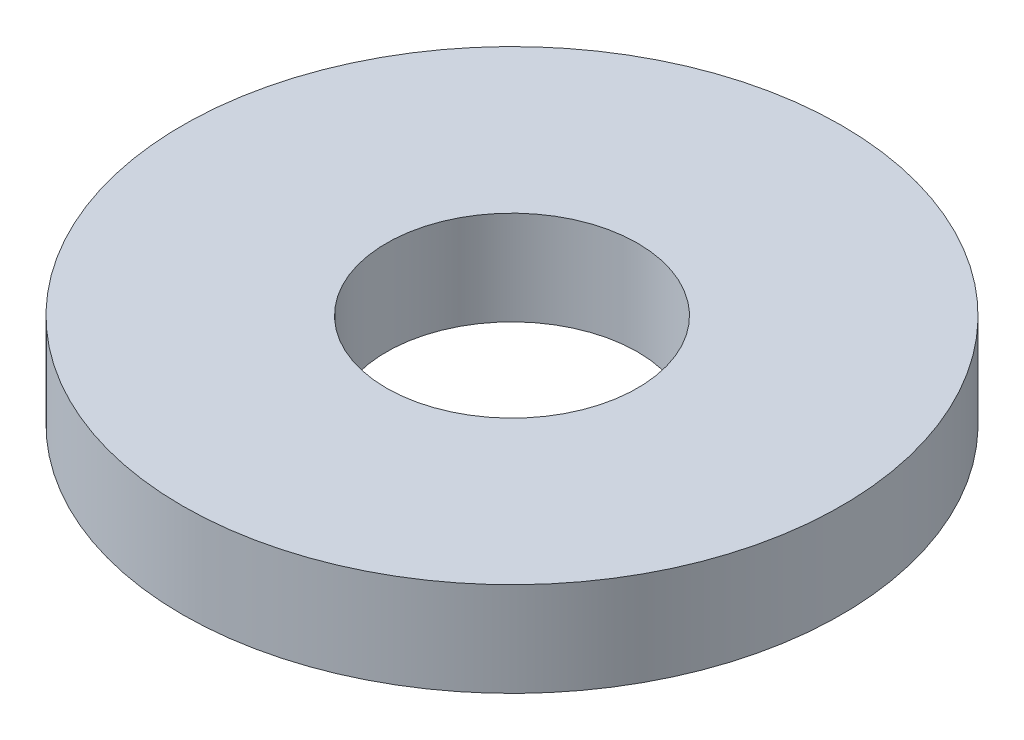
SolidWorks part; units mm, degrees
ref_plane "Front Plane" through (0, 0, 0) normal (0, 0, 1) x (1, 0, 0)
ref_plane "Top Plane" through (0, 0, 0) normal (0, 1, 0) x (1, 0, 0)
ref_plane "Right Plane" through (0, 0, 0) normal (1, 0, 0) x (0, 0, -1)
sketch "Sketch1" plane through (0, 0, 0) normal (0, 1, 0) x (1, 0, 0)
  circle A0 centre (0, 0) radius 4
  circle A1 centre (0, 0) radius 10.5
  dimension "D1" = 8
  dimension "D2" = 21
extrude "Boss-Extrude1" add sketch "Sketch1" along normal blind 3
